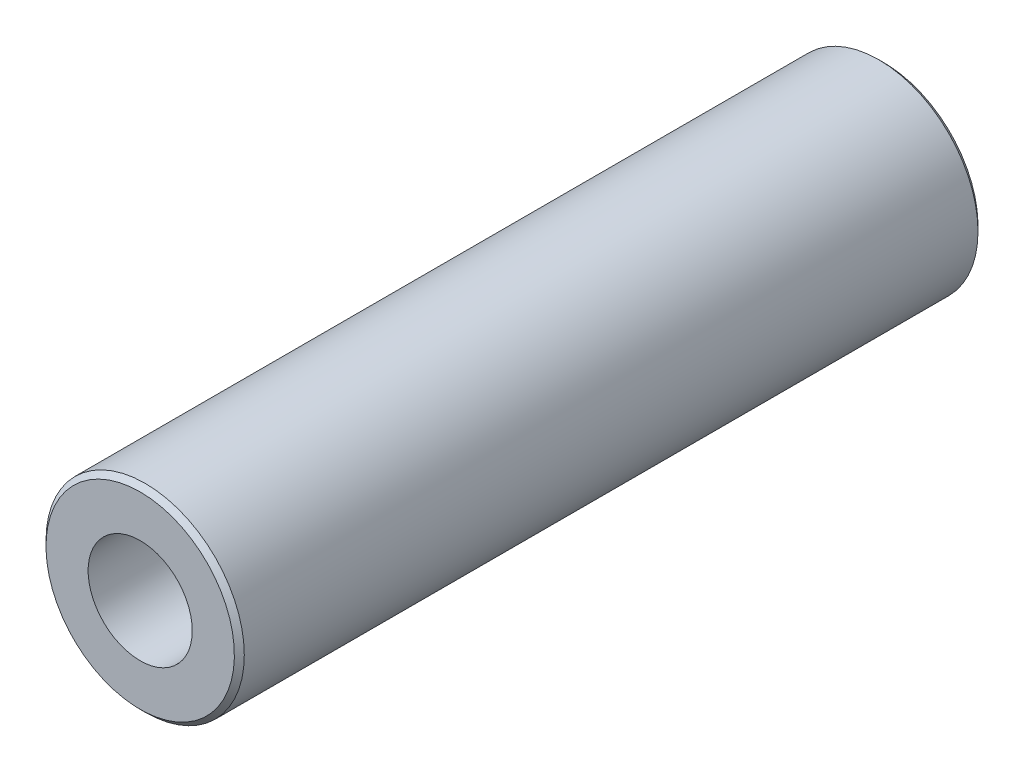
SolidWorks part; units mm, degrees
material "AISI 304"
ref_plane "前视基准面" through (0, 0, 0) normal (0, 0, 1) x (1, 0, 0)
ref_plane "上视基准面" through (0, 0, 0) normal (0, 1, 0) x (1, 0, 0)
ref_plane "右视基准面" through (0, 0, 0) normal (1, 0, 0) x (0, 0, -1)
sketch "草图1" plane through (0, 0, 0) normal (1, 0, 0) x (0, 0, -1)
  line L0 (-15, 0) -> (15, 0) construction
  line L1 (15, 0) -> (15, 4)
  line L2 (15, 4) -> (-15, 4)
  line L3 (-15, 4) -> (-15, 0)
  line L4 (15, 0) -> (-15, 0)
  point P4 (0, 0)
  dimension "不锈钢柱大经" = 8
  dimension "不锈钢柱长度" = 30
revolve "旋转1" add sketch "草图1" angle 360 about L0
hole_wizard " 螺纹孔1" positions "草图2" profile "草图3" tap size "M3" standard "GB"
sketch "草图2" plane through (0, 0, 15) normal (0, 0, 1) x (1, 0, 0)
  point P0 (0, 0)
sketch "草图3" plane through (0, 0, 15) normal (1, 0, 0) x (0, -1, 0)
  line L0 (0, 0) -> (0, 14.7618)
  line L1 (0, 14.7618) -> (2.1, 13.5)
  line L2 (2.1, 13.5) -> (2.1, 0)
  line L5 (2.1, 0) -> (0, 0)
  line L10 (0, 14.7618) -> (-2.1, 13.5) construction
  line L11 (0, -6.35) -> (0, 107.95) construction
  dimension "螺纹孔钻头直径" = 4.2
  dimension "螺纹孔钻头深度" = 13.5
  dimension "导头角度" = 118
cosmetic thread "孔螺蚊线1"
mirror "镜向1" about plane through (0, 0, 0) normal (0, 0, 1) of " 螺纹孔1"
cosmetic thread "孔螺蚊线2" parameters "D1"=12, "D2"=5.4
chamfer "倒角1" distance 0.2 angle 45 2 edges at (0, -4, -15) (0, -4, 15)
